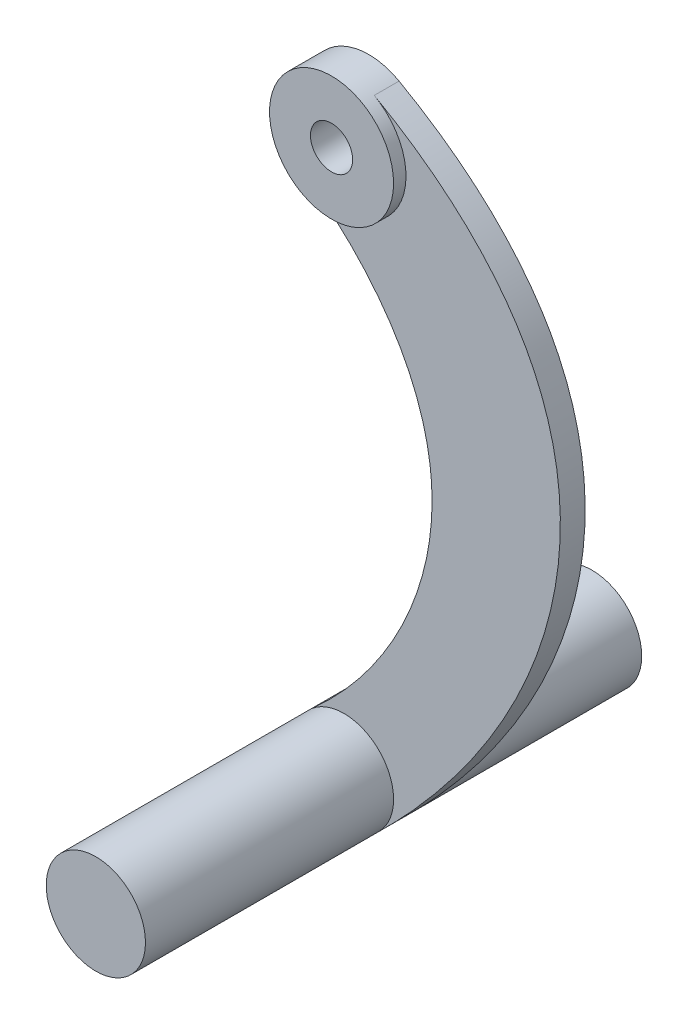
SolidWorks part; units mm, degrees
ref_plane "Спереди" through (0, 0, 0) normal (0, 0, 1) x (1, 0, 0)
ref_plane "Сверху" through (0, 0, 0) normal (0, 1, 0) x (1, 0, 0)
ref_plane "Справа" through (0, 0, 0) normal (1, 0, 0) x (0, 0, -1)
other "Configuration Table"
sketch "Sketch1" plane through (0, 0, 0) normal (0, 0, 1) x (1, 0, 0)
  circle A0 centre (0, 0) radius 4.25
  circle A1 centre (0, 0) radius 12.5
  dimension "D1" = 8.5
  dimension "D2" = 25
extrude "Boss-Extrude1" add sketch "Sketch1" along normal blind 2.5
sketch "Sketch2" plane through (0, 0, 0) normal (0, 0, -1) x (-1, 0, 0)
  line L0 (0, 32.4083) -> (0, -121.3898) construction
  arc A3 (-6.1064, 10.907) -> (7.4068, -10.0692) centre (0, 0) cw
  arc A4 (6.6111, -102.4971) -> (-7.0028, -117.1387) centre (0, -110) cw
  spline S2 degree 3 poles (-6.1064, 10.907) (-20.6217, 2.7804) (-57.0301, -32.0145) (-40.003, -84.7667) (-7.0028, -117.1387) knots 0 0 0 0 0.302024 1 1 1 1
  spline S3 degree 3 poles (7.4068, -10.0692) (-7.9799, -21.3875) (-26.8557, -52.6463) (-9.4398, -88.354) (6.6111, -102.4971) knots 0 0 0 0 0.455822 1 1 1 1
  dimension "D1" = 110
extrude "Boss-Extrude2" add sketch "Sketch2" along normal blind 5
sketch "Sketch3" plane through (0, 0, 0) normal (0, 0, 1) x (1, 0, 0)
  circle A0 centre (0, -110) radius 10
  point P2 (0, 0)
  point P3 (0, 0)
  point P5 (0, 0)
  dimension "D1" = 20
  dimension "D2" = 110
extrude "Boss-Extrude3" add sketch "Sketch3" along normal blind 50 and the other way blind 50
sketch "Sketch4" plane through (0, 0, 0) normal (0, 0, 1) x (1, 0, 0)
  circle A0 centre (0, 0) radius 4.25
  dimension "D1" = 8.5
extrude "Cut-Extrude1" cut sketch "Sketch4" against normal blind 40
